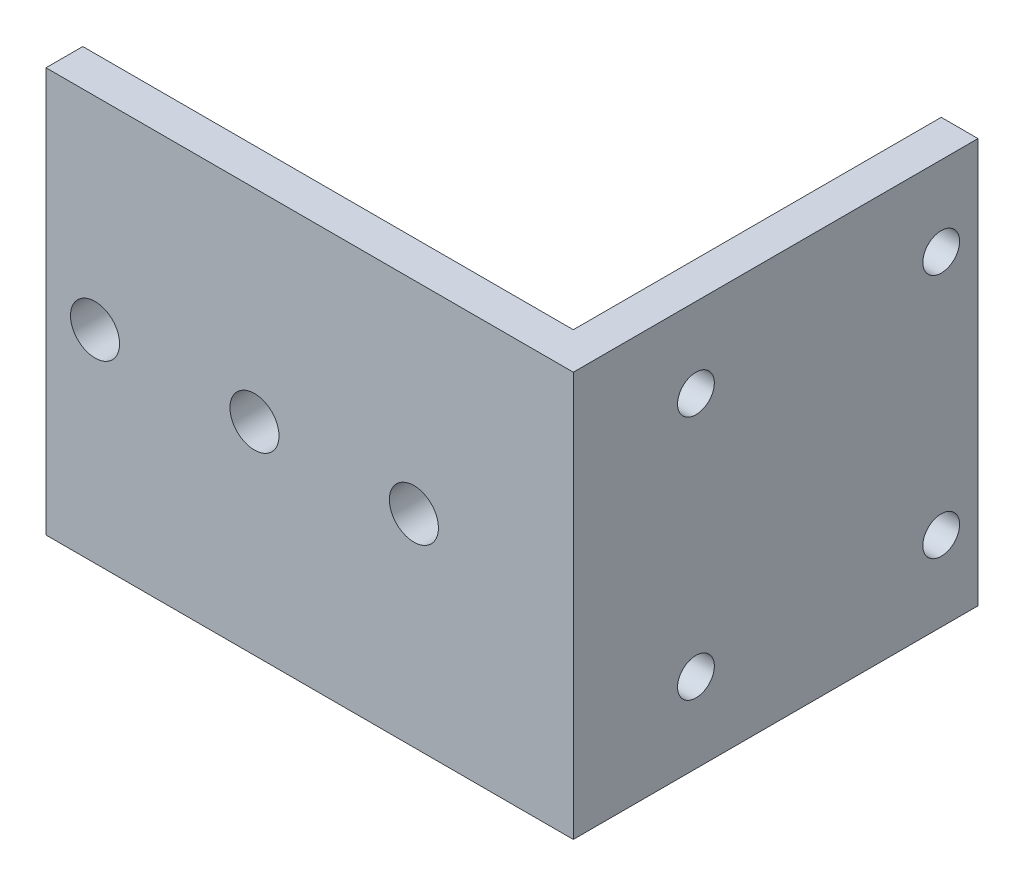
SolidWorks part; units mm, degrees
ref_plane "前视基准面" through (0, 0, 0) normal (0, 0, 1) x (1, 0, 0)
ref_plane "上视基准面" through (0, 0, 0) normal (0, 1, 0) x (1, 0, 0)
ref_plane "右视基准面" through (0, 0, 0) normal (1, 0, 0) x (0, 0, -1)
sketch "草图1" plane through (0, 0, 0) normal (0, 1, 0) x (1, 0, 0)
  line L0 (0, 0) -> (43, 0)
  line L1 (43, 0) -> (43, 33)
  line L2 (43, 33) -> (40, 33)
  line L3 (40, 33) -> (40, 3)
  line L4 (40, 3) -> (0, 3)
  line L5 (0, 3) -> (0, 0)
  dimension "D1" = 30
  dimension "D2" = 40
  dimension "D3" = 3
  dimension "D4" = 3
extrude "凸台-拉伸1" add sketch "草图1" along normal blind 33
sketch "草图2" plane through (40, 0, 0) normal (-1, 0, 0) x (0, 0, 1)
  line L0 (-33, 0) -> (-3, 0) construction
  line L1 (-33, 33) -> (-33, 0) construction
  circle A0 centre (-30, 6.5) radius 1.5
  circle A1 centre (-30, 26.5) radius 1.5
  circle A2 centre (-10, 6.5) radius 1.5
  circle A3 centre (-10, 26.5) radius 1.5
  dimension "D6" = 3
  dimension "D1" = 20
  dimension "D2" = 20
  dimension "D3" = 6.5
  dimension "D4" = 3
  dimension "D5" = 20
extrude "切除-拉伸1" cut sketch "草图2" against normal up to next
sketch "草图3" plane through (0, 0, -3) normal (0, 0, -1) x (-1, 0, 0)
  line L0 (-40, 33) -> (0, 33) construction
  line L1 (0, 33) -> (0, 0) construction
  circle A0 centre (-4, 16.5) radius 2
  circle A1 centre (-30, 16.5) radius 2
  circle A2 centre (-17, 16.5) radius 2
  dimension "D2" = 4
  dimension "D5" = 4
  dimension "D6" = 4
  dimension "D1" = 16.5
  dimension "D3" = 26
  dimension "D4" = 30
  dimension "D7" = 13
extrude "切除-拉伸2" cut sketch "草图3" against normal up to next
